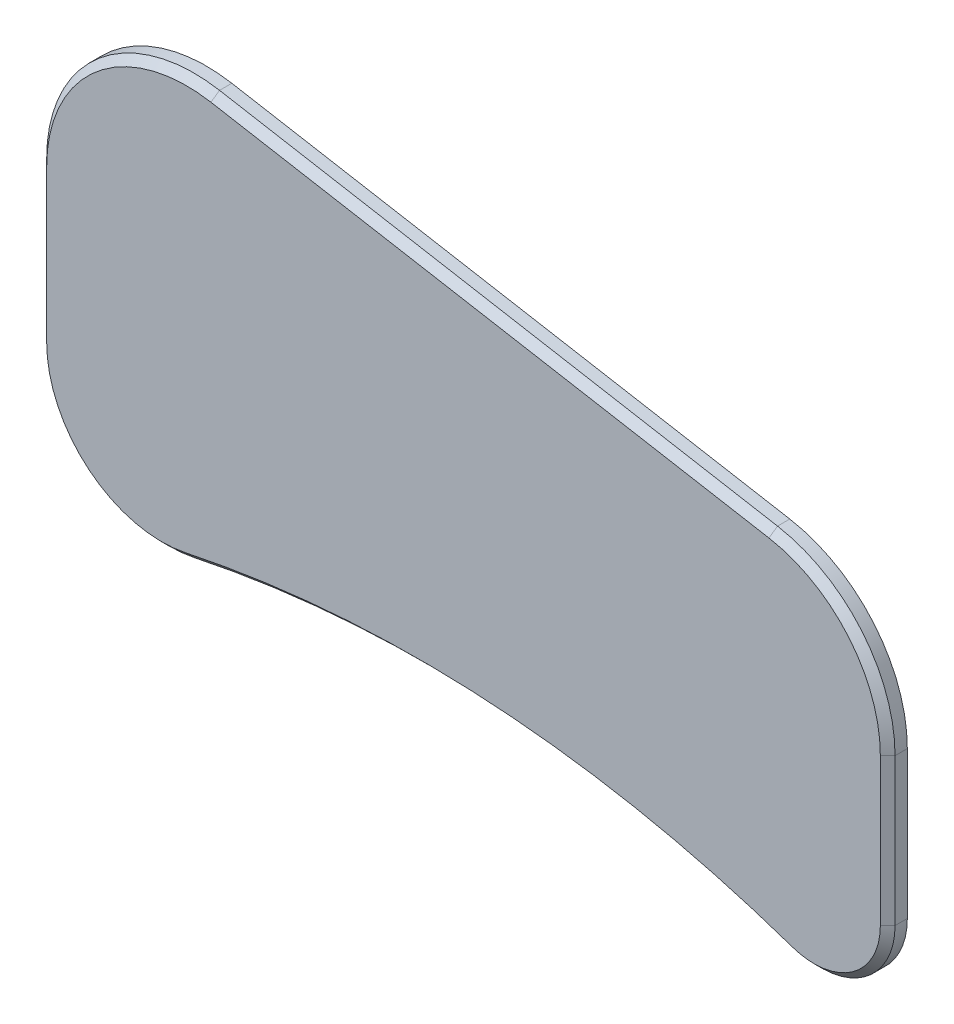
SolidWorks part; units mm, degrees
ref_plane "Front Plane" through (0, 0, 0) normal (0, 0, 1) x (1, 0, 0)
ref_plane "Top Plane" through (0, 0, 0) normal (0, 1, 0) x (1, 0, 0)
ref_plane "Right Plane" through (0, 0, 0) normal (1, 0, 0) x (0, 0, -1)
sketch "Sketch1" plane through (0, 0, 0) normal (0, 0, 1) x (1, 0, 0)
  line L0 (-48.9642, 39.0811) -> (59.0358, 20.0378) construction
  line L1 (83, -8.5217) -> (83, -33.5217) construction
  line L2 (-54.7487, 40.101) -> (59.0358, 20.0378)
  line L3 (83, -8.5217) -> (83, -38.5217)
  line L13 (-68, -36.5217) -> (-80, -36.5217) construction
  line L14 (-90, -33.5217) -> (-90, 10.5217)
  line L15 (-90, -20.5217) -> (-90, 10.5217)
  line L16 (68, -53.5217) -> (-69.3957, -53.5217) construction
  arc A0 (83, -8.5217) -> (59.0358, 20.0378) centre (54, -8.5217) ccw construction
  arc A1 (83, -8.5217) -> (59.0358, 20.0378) centre (54, -8.5217) ccw
  arc A6 (-90, 10.5217) -> (-54.7487, 40.101) centre (-59.9643, 10.5217) cw
  arc A7 (-90, -20.5217) -> (-59.8284, -44.9809) centre (-65, -20.5217) ccw
  arc A8 (83, -38.5217) -> (63.0867, -52.6942) centre (68, -38.5217) cw
  arc A9 (63.0867, -52.6942) -> (-59.8284, -44.9809) centre (-12.2498, -270.0059) ccw
  point P16 (-65, -45.5217)
  dimension "D2" = 30.0357
  dimension "D3" = 15
  dimension "D4" = 25
  dimension "D5" = 230
  dimension "D6" = 9
  dimension "D7" = 8
  dimension "D1" = 7
extrude "Boss-Extrude1" add sketch "Sketch1" along normal blind 4
chamfer "Chamfer1" distance 1.5 angle 45 8 edges at (76.6977, -50.7425, 4) (83, -23.5217, 4) (2.155, -40.4575, 4) (76.2153, 10.1192, 4) (-80.7434, -39.9419, 4) (2.1436, 30.0694, 4) (-90, -5, 4) (-79.2709, 33.5303, 4)
